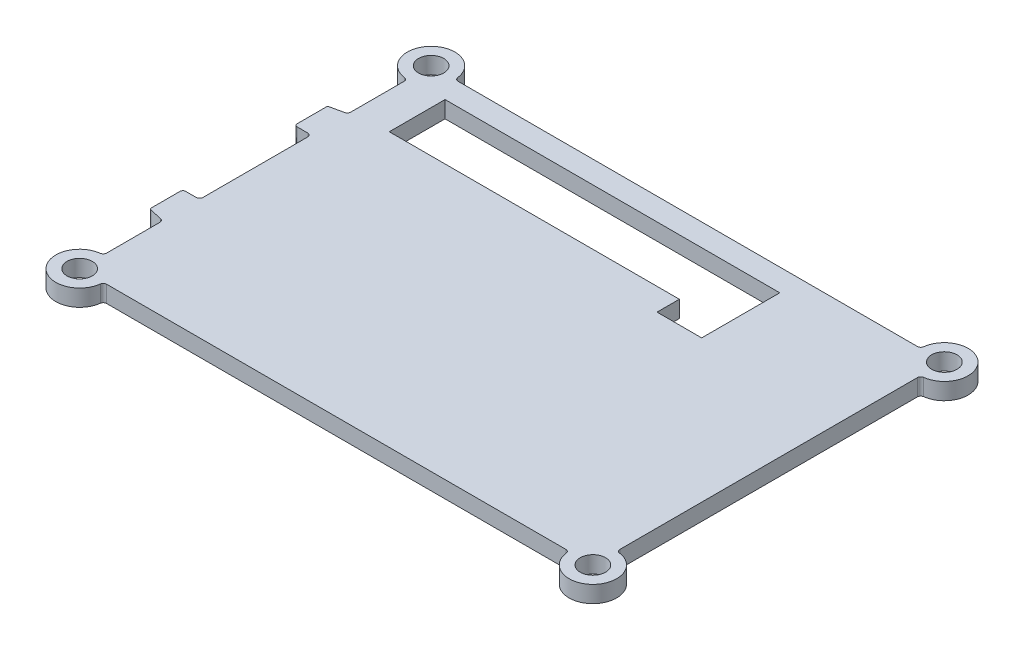
SolidWorks part; units mm, degrees
material "Balsa"
ref_plane "Front Plane" through (0, 0, 0) normal (0, 0, 1) x (1, 0, 0)
ref_plane "Top Plane" through (0, 0, 0) normal (0, 1, 0) x (1, 0, 0)
ref_plane "Right Plane" through (0, 0, 0) normal (1, 0, 0) x (0, 0, -1)
sketch "Sketch1" plane through (0, 0, 0) normal (0, 1, 0) x (1, 0, 0)
  line L0 (46, 0) -> (46, -63) construction
  line L5 (4.265, 0) -> (87.735, 0)
  line L6 (3.2, -3.25) -> (88.8, -3.25) construction
  line L7 (3.2, -3.25) -> (3.2, -59.75) construction
  line L8 (3.2, -59.75) -> (88.8, -59.75) construction
  line L9 (88.8, -3.25) -> (88.8, -59.75) construction
  line L10 (3.2, -3.25) -> (88.8, -59.75) construction
  line L11 (3.2, -59.75) -> (88.8, -3.25) construction
  line L12 (0, -4.265) -> (0, -58.735)
  line L14 (92, -4.265) -> (92, -58.735)
  line L15 (4.265, -63) -> (87.735, -63)
  circle A0 centre (0, 0) radius 2.265
  circle A1 centre (92, 0) radius 2.265
  circle A2 centre (92, -63) radius 2.265
  circle A3 centre (0, -63) radius 2.265
  arc A4 (4.265, 0) -> (0, -4.265) centre (0, 0) ccw
  arc A5 (92, -4.265) -> (87.735, 0) centre (92, 0) ccw
  arc A6 (87.735, -63) -> (92, -58.735) centre (92, -63) ccw
  arc A7 (0, -58.735) -> (4.265, -63) centre (0, -63) ccw
  point P7 (46, -31.5)
  dimension "D5" = 4.53
  dimension "D6" = 2
  dimension "D1" = 92
  dimension "D2" = 63
  dimension "D3" = 85.6
  dimension "D4" = 56.5
extrude "Boss-Extrude1" add sketch "Sketch1" along normal blind 3
sketch "Sketch2" plane through (0, 3, 0) normal (0, 1, 0) x (1, 0, 0)
  line L0 (87.735, 0) -> (4.265, 0) construction
  line L1 (6.5, -4) -> (66.5, -4)
  line L2 (6.5, -4) -> (6.5, -14)
  line L3 (6.5, -14) -> (58.5, -14)
  line L4 (66.5, -4) -> (66.5, -14)
  line L5 (0, -4.265) -> (0, -58.735) construction
  line L7 (66.5, -14) -> (66.5, -18)
  line L8 (66.5, -18) -> (58.5, -18)
  line L9 (58.5, -14) -> (58.5, -18)
  dimension "D1" = 60
  dimension "D2" = 4
  dimension "D3" = 10
  dimension "D4" = 4
  dimension "D5" = 8
  dimension "D6" = 6.5
extrude "Cut-Extrude1" cut sketch "Sketch2" against normal blind 3
sketch "Sketch3" plane through (0, 3, 0) normal (0, 1, 0) x (1, 0, 0)
  line L0 (0, -31.5) -> (92, -31.5) construction
  line L1 (0, -4.265) -> (0, -58.735) construction
  line L2 (92, -58.735) -> (92, -4.265) construction
  line L4 (0, -21.5) -> (6.5, -21.5)
  line L5 (0, -21.5) -> (0, -41.5)
  line L6 (0, -41.5) -> (6.5, -41.5)
  line L7 (6.5, -21.5) -> (6.5, -41.5)
  point P11 (0, -31.5)
  dimension "D1" = 6.5
  dimension "D2" = 20
extrude "Cut-Extrude2" cut sketch "Sketch3" against normal blind 3
sketch "Sketch4" plane through (0, 3, 0) normal (0, 1, 0) x (1, 0, 0)
  line L0 (-2.7, -15.5) -> (0, -14.9)
  line L1 (0, -21.5) -> (-2.5, -21.5)
  line L2 (0, -21.5) -> (0, -14.9)
  line L4 (-3, -21) -> (-3, -15.8)
  line L5 (6.5, -31.5) -> (-13.34, -31.5) construction
  line L6 (6.5, -41.5) -> (6.5, -21.5) construction
  line L7 (-3, -42) -> (-3, -47.2)
  line L8 (0, -41.5) -> (-2.5, -41.5)
  line L9 (0, -41.5) -> (0, -48.1)
  line L10 (-2.7, -47.5) -> (0, -48.1)
  arc A0 (-3, -21) -> (-2.5, -21.5) centre (-2.5, -21) ccw
  arc A1 (-3, -15.8) -> (-2.7, -15.5) centre (-2.7, -15.8) cw
  arc A2 (-3, -47.2) -> (-2.7, -47.5) centre (-2.7, -47.2) ccw
  arc A3 (-3, -42) -> (-2.5, -41.5) centre (-2.5, -42) cw
  point P7 (-3, -21.5)
  point P10 (-3, -15.5)
  dimension "D3" = 0.5
  dimension "D4" = 0.3
  dimension "D1" = 3
  dimension "D2" = 6
  dimension "D5" = 6.6
extrude "Boss-Extrude2" add sketch "Sketch4" against normal blind 3
sketch "Sketch5" plane through (0, 3, 0) normal (0, 1, 0) x (1, 0, 0)
  line L0 (6.5, -21.5) -> (-2.5, -21.5) construction
  line L1 (0, -21.5) -> (6.5, -21.5)
  line L2 (0, -21.5) -> (0, -41.5)
  line L3 (0, -41.5) -> (6.5, -41.5)
  line L4 (6.5, -21.5) -> (6.5, -41.5)
extrude "Boss-Extrude3" add sketch "Sketch5" against normal blind 3
sketch "Sketch6" plane through (0, 3, 0) normal (0, 1, 0) x (1, 0, 0)
  line L0 (0, -21.5) -> (0, -41.5) construction
  line L1 (4, -22) -> (8, -22)
  line L2 (4, -22) -> (4, -43.5)
  line L3 (4, -43.5) -> (8, -43.5)
  line L4 (8, -22) -> (8, -43.5)
  line L5 (6.5, -14) -> (58.5, -14) construction
  line L6 (4.265, -63) -> (87.735, -63) construction
  line L7 (42, -37.5) -> (46, -37.5)
  line L8 (42, -37.5) -> (42, -59)
  line L9 (42, -59) -> (46, -59)
  line L10 (46, -37.5) -> (46, -59)
  line L11 (0, -48.1) -> (0, -58.735) construction
  line L12 (8, -32.75) -> (43.4277, -32.75) construction
  line L14 (13.7139, -20.75) -> (37.7139, -20.75) construction
  line L15 (13.7139, -20.75) -> (13.7139, -44.75) construction
  line L16 (13.7139, -44.75) -> (37.7139, -44.75) construction
  line L17 (37.7139, -20.75) -> (37.7139, -44.75) construction
  line L18 (13.7139, -20.75) -> (37.7139, -44.75) construction
  line L19 (13.7139, -44.75) -> (37.7139, -20.75) construction
  circle A0 centre (25.7139, -32.75) radius 13.5
  circle A1 centre (13.7139, -20.75) radius 1.25
  circle A2 centre (37.7139, -20.75) radius 1.25
  circle A3 centre (37.7139, -44.75) radius 1.25
  circle A4 centre (13.7139, -44.75) radius 1.25
  point P20 (25.7139, -32.75)
  dimension "D9" = 27
  dimension "D10" = 2.5
  dimension "D1" = 4
  dimension "D2" = 21.5
  dimension "D3" = 4
  dimension "D4" = 8
  dimension "D5" = 4
  dimension "D6" = 21.5
  dimension "D7" = 4
  dimension "D8" = 42
  dimension "D11" = 24
  dimension "D12" = 24
fillet "Fillet1" radius 0.6 12 edges at (87.735, 1.5, 0) (92, 1.5, 4.265) (92, 1.5, 58.735) (87.735, 1.5, 63) (4.265, 1.5, 63) (0, 1.5, 58.735) (0, 1.5, 48.1) (0, 1.5, 41.5) (0, 1.5, 21.5) (0, 1.5, 14.9) (4.265, 1.5, 0) (0, 1.5, 4.265)
